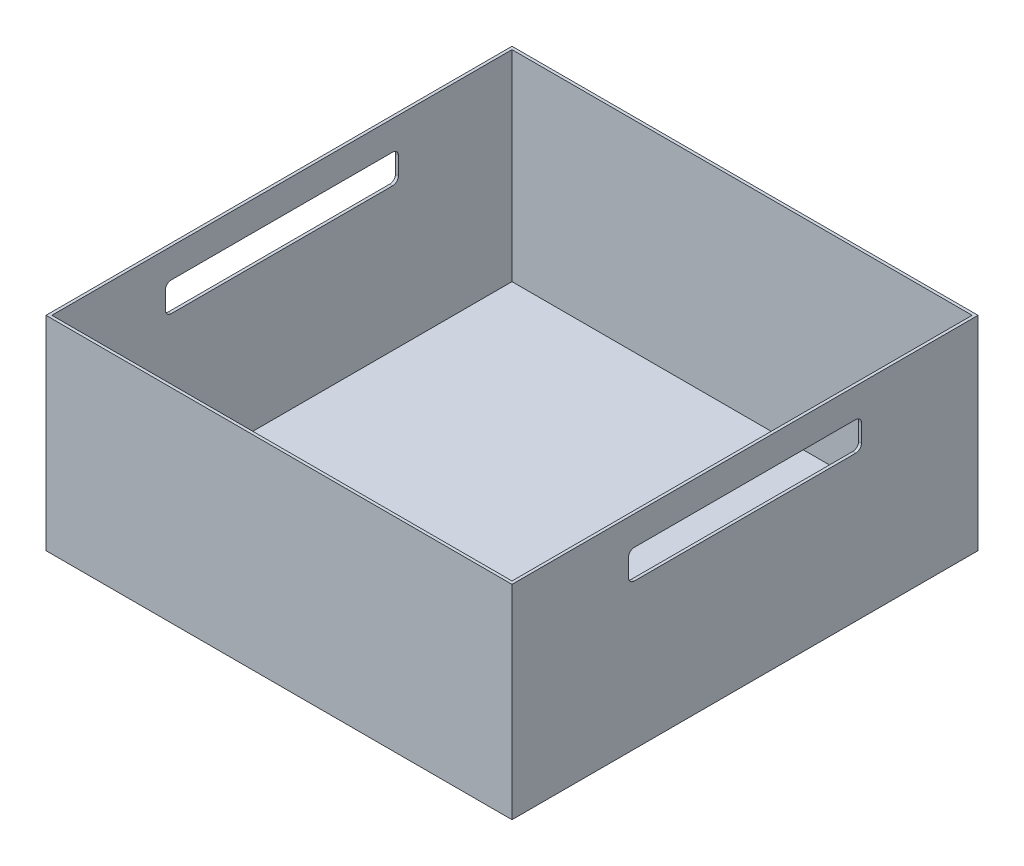
SolidWorks part; units mm, degrees
ref_plane "Ebene vorne" through (0, 0, 0) normal (0, 0, 1) x (1, 0, 0)
ref_plane "Ebene oben" through (0, 0, 0) normal (0, 1, 0) x (1, 0, 0)
ref_plane "Ebene rechts" through (0, 0, 0) normal (1, 0, 0) x (0, 0, -1)
sketch "Skizze1" plane through (0, 0, 0) normal (0, 1, 0) x (1, 0, 0)
  line L1 (0, 0) -> (800, 0)
  line L2 (0, 0) -> (0, 800)
  line L3 (0, 800) -> (800, 800)
  line L4 (800, 0) -> (800, 800)
  dimension "D1" = 800
  dimension "D2" = 800
extrude "Aufsatz-Linear austragen1" add sketch "Skizze1" along normal blind 350
sketch "Skizze2" plane through (0, 350, 0) normal (0, 1, 0) x (1, 0, 0)
  line L0 (800, 800) -> (0, 800) construction
  line L1 (5, 795) -> (795, 795)
  line L2 (5, 795) -> (5, 5)
  line L3 (5, 5) -> (795, 5)
  line L4 (795, 795) -> (795, 5)
  line L5 (0, 0) -> (800, 0) construction
  line L6 (0, 800) -> (0, 0) construction
  line L7 (800, 0) -> (800, 800) construction
  dimension "D1" = 5
  dimension "D2" = 5
  dimension "D3" = 5
  dimension "D4" = 5
extrude "Schnitt-Linear austragen1" cut sketch "Skizze2" against normal blind 345
sketch "Skizze3" plane through (800, 0, 0) normal (1, 0, 0) x (0, 0, -1)
  line L0 (0, 350) -> (0, 0) construction
  line L1 (210, 300) -> (590, 300)
  line L2 (200, 290) -> (200, 260)
  line L3 (210, 250) -> (590, 250)
  line L4 (600, 290) -> (600, 260)
  line L5 (800, 350) -> (800, 0) construction
  line L6 (0, 350) -> (800, 350) construction
  arc A0 (210, 300) -> (200, 290) centre (210, 290) ccw
  arc A1 (600, 290) -> (590, 300) centre (590, 290) ccw
  arc A2 (600, 260) -> (590, 250) centre (590, 260) cw
  arc A3 (210, 250) -> (200, 260) centre (210, 260) cw
  point P12 (200, 300)
  point P19 (200, 250)
  dimension "D5" = 10
  dimension "D6" = 10
  dimension "D7" = 10
  dimension "D8" = 10
  dimension "D1" = 200
  dimension "D2" = 200
  dimension "D3" = 50
  dimension "D4" = 50
extrude "Schnitt-Linear austragen2" cut sketch "Skizze3" against normal through all both and the other way through all
